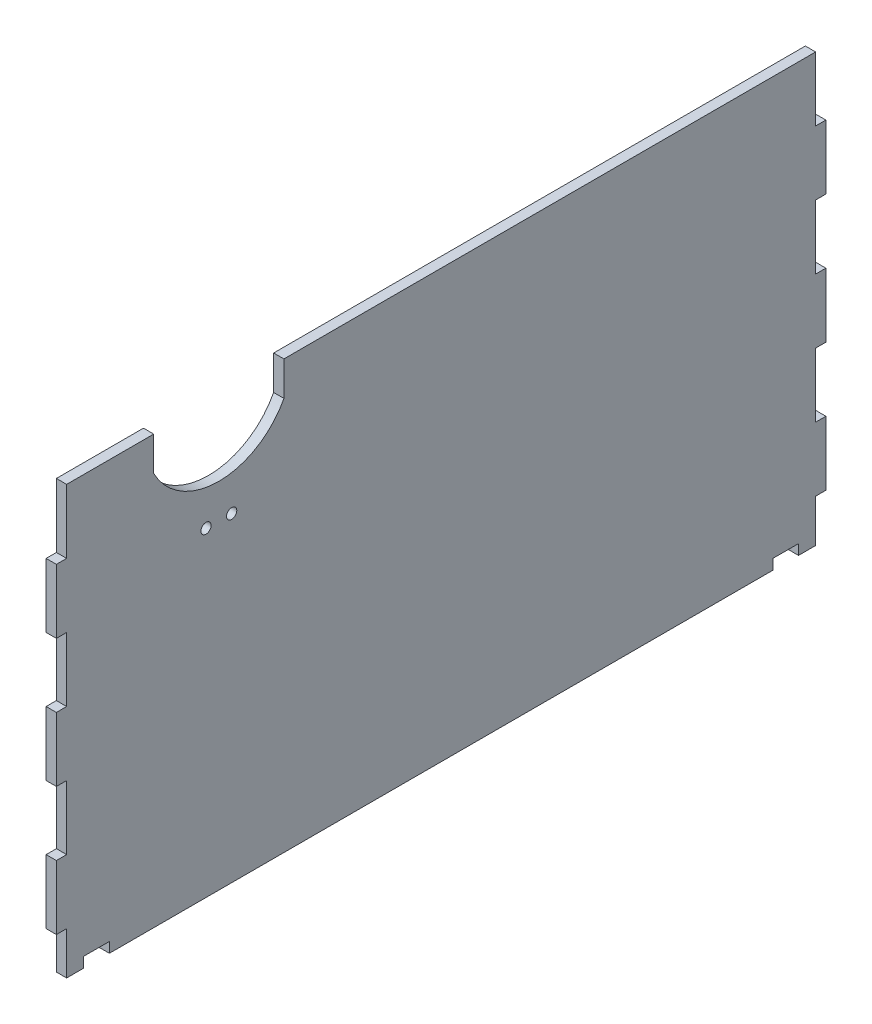
SolidWorks part; units mm, degrees
ref_plane "Front" through (0, 0, 0) normal (0, 0, 1) x (1, 0, 0)
ref_plane "Top" through (0, 0, 0) normal (0, 1, 0) x (1, 0, 0)
ref_plane "Right" through (0, 0, 0) normal (1, 0, 0) x (0, 0, -1)
sketch "Sketch1" plane through (0, 0, 0) normal (1, 0, 0) x (0, 0, -1)
  line L1 (0, 0) -> (-450, 0)
  line L2 (0, 0) -> (0, 250)
  line L3 (0, 250) -> (-450, 250)
  line L4 (-450, 0) -> (-450, 250)
  dimension "D1" = 450
  dimension "D2" = 250
extrude "Boss-Extrude1" add sketch "Sketch1" along normal blind 6
sketch "Sketch2" plane through (6, 0, 0) normal (1, 0, 0) x (0, 0, -1)
  line L0 (-450, 250) -> (-450, 0) construction
  line L1 (-450, 250) -> (-444, 250)
  line L2 (-450, 250) -> (-450, 212.5)
  line L3 (-450, 212.5) -> (-444, 212.5)
  line L4 (-444, 250) -> (-444, 212.5)
  line L5 (0, 250) -> (-450, 250) construction
  dimension "D1" = 6
  dimension "D2" = 37.5
extrude "Cut-Extrude1" cut sketch "Sketch2" against normal through all
pattern_linear "LPattern1" count 4 spacing 75 along (0, -1, 0) count 2 spacing 444 along (0, 0, -1) of "Cut-Extrude1"
sketch "Sketch3" plane through (6, 0, 0) normal (1, 0, 0) x (0, 0, -1)
  line L0 (-444, 0) -> (-6, 0) construction
  line L1 (-434, 0) -> (-419, 0)
  line L2 (-434, 0) -> (-434, 6)
  line L3 (-434, 6) -> (-419, 6)
  line L4 (-419, 0) -> (-419, 6)
  line L6 (-444, 62.5) -> (-444, 100) construction
  dimension "D1" = 10
  dimension "D2" = 15
  dimension "D3" = 6
extrude "Cut-Extrude2" cut sketch "Sketch3" against normal through all
pattern_linear "LPattern2" count 2 spacing 403 along (0, 0, -1) of "Cut-Extrude2"
sketch "Sketch4" plane through (6, 0, 0) normal (1, 0, 0) x (0, 0, -1)
  line L0 (-393.0657, 230) -> (-316.9343, 230) construction
  line L1 (-355, 250) -> (-355, 207) construction
  line L2 (-450, 212.5) -> (-450, 175) construction
  line L3 (-393.0657, 230) -> (-393.0657, 250)
  line L4 (-6, 250) -> (-444, 250) construction
  line L5 (-393.0657, 250) -> (-316.9343, 250)
  line L6 (-316.9343, 250) -> (-316.9343, 230)
  arc A0 (-393.0657, 230) -> (-316.9343, 230) centre (-355, 250) ccw
  circle A1 centre (-362.5, 187) radius 3
  circle A3 centre (-347.5, 187) radius 3
  dimension "D4" = 63
  dimension "D1" = 43
  dimension "D6" = 6
  dimension "D2" = 20
  dimension "D3" = 95
  dimension "D5" = 7.5
extrude "Cut-Extrude3" cut sketch "Sketch4" against normal blind 10
